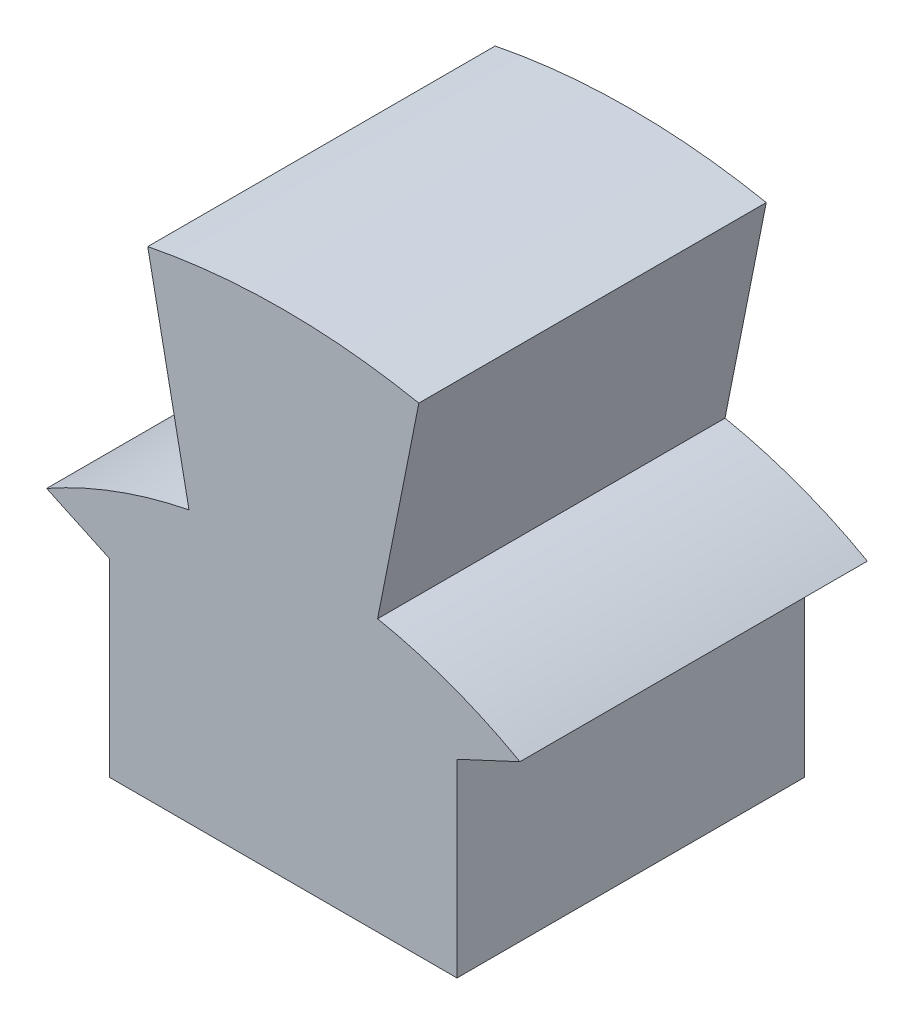
SolidWorks part; units mm, degrees
ref_plane "Plano frontal" through (0, 0, 0) normal (0, 0, 1) x (1, 0, 0)
ref_plane "Plano superior" through (0, 0, 0) normal (0, 1, 0) x (1, 0, 0)
ref_plane "Plano direito" through (0, 0, 0) normal (1, 0, 0) x (0, 0, -1)
sketch "Esboço1" plane through (0, 0, 0) normal (0, 0, 1) x (1, 0, 0)
  line L0 (-3, -8.5) -> (-3, -5.2281)
  line L18 (-3, -5.2281) -> (-3, -8.5)
  line L19 (-3, -8.5) -> (3, -8.5)
  line L20 (3, -8.5) -> (3, -5.2281)
  line L21 (3, -5.2281) -> (4.0874, -4.7211)
  line L22 (-1.6286, -3.8124) -> (-2.3411, -0.2306)
  line L23 (0, -12) -> (-4.5922, -0.9134) construction
  line L24 (0, -12) -> (-2.3411, -0.2306) construction
  line L26 (0, -12) -> (4.5922, -0.9134) construction
  line L27 (0, -12) -> (2.3411, -0.2306) construction
  line L28 (0, -12) -> (-5.8755, -1.5368) construction
  line L29 (2.3411, -0.2306) -> (1.6286, -3.8124)
  line L30 (2.3411, -0.2306) -> (1.6286, -3.8124)
  line L32 (-2.3411, -0.2306) -> (-1.6286, -3.8124)
  line L33 (-4.0874, -4.7211) -> (-3, -5.2281)
  line L34 (4.0874, -4.7211) -> (3, -5.2281)
  line L35 (3, -8.5) -> (-3, -8.5)
  line L36 (3, -5.2281) -> (3, -8.5)
  arc A2 (-5.8755, -1.5368) -> (7.1177, -2.3388) centre (0, -12) cw construction
  arc A3 (4.0874, -4.7211) -> (3.1947, -4.2874) centre (0, -12) ccw
  arc A5 (7.6985, -8.7716) -> (-4.0874, -4.7211) centre (0, -12) ccw
  arc A6 (0, 0) -> (2.3411, -0.2306) centre (0, -12) cw
  arc A7 (1.6286, -3.8124) -> (3.1947, -4.2874) centre (0, -12) cw
  arc A8 (0, 0) -> (-2.3411, -0.2306) centre (0, -12) ccw
  arc A9 (-1.6286, -3.8124) -> (-3.1947, -4.2874) centre (0, -12) ccw
  arc A10 (-3.1947, -4.2874) -> (-4.0874, -4.7211) centre (0, -12) ccw
  arc A11 (-4.0874, -4.7211) -> (-1.6286, -3.8124) centre (0, -12) cw
  arc A12 (-2.3411, -0.2306) -> (2.3411, -0.2306) centre (0, -12) cw
  arc A13 (1.6286, -3.8124) -> (4.0874, -4.7211) centre (0, -12) cw
  dimension "D13" = 8.348
  dimension "D14" = 12
  dimension "D2" = 65
  dimension "D3" = 3.2719
  dimension "D4" = 6
  dimension "D5" = 8.5
  dimension "D6" = 3
  dimension "D7" = 22.5
  dimension "D8" = 11.25
  dimension "D10" = 22.5
  dimension "D11" = 11.25
  dimension "D15" = 65
extrude "Ressalto-extrusão1" add sketch "Esboço1" along normal blind 6 contours A3 A5 L33 L0 L19 L20 L21 | A6 A8 L22 A5 L29
